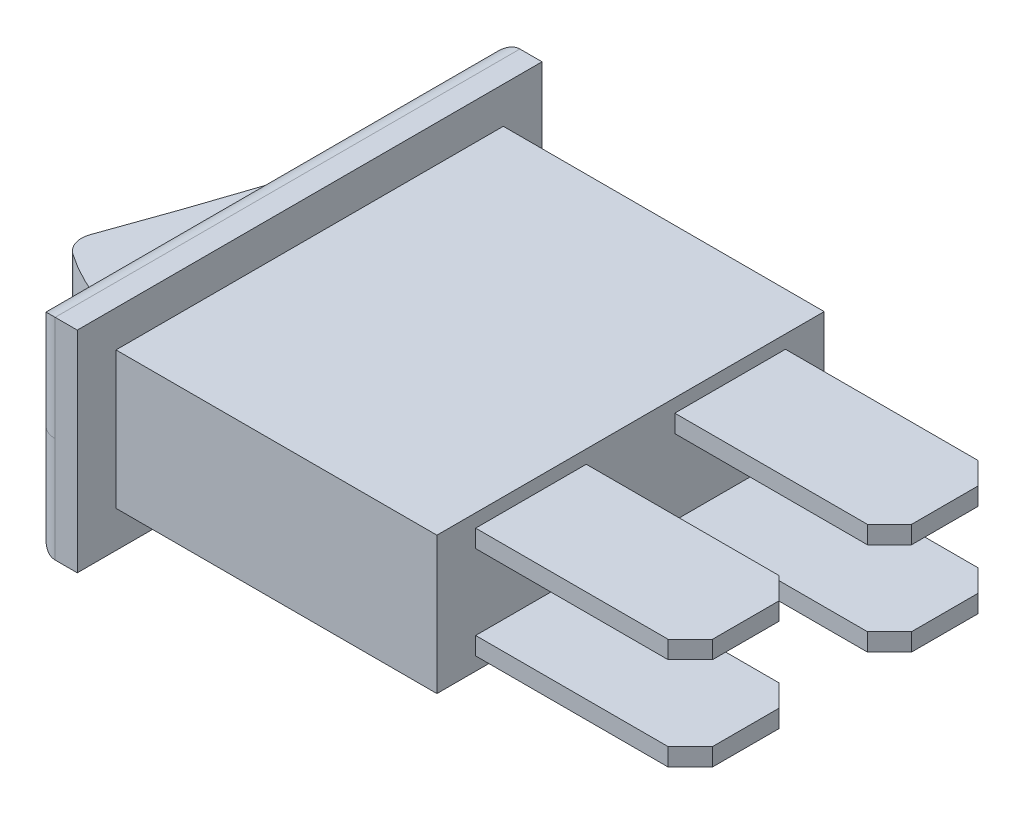
SolidWorks part; units mm, degrees
material "ABS"
ref_plane "Plan de face" through (0, 0, 0) normal (0, 0, 1) x (1, 0, 0)
ref_plane "Plan de dessus" through (0, 0, 0) normal (0, 1, 0) x (1, 0, 0)
ref_plane "Plan de droite" through (0, 0, 0) normal (1, 0, 0) x (0, 0, -1)
sketch "Esquisse1" plane through (0, 0, 0) normal (0, 1, 0) x (1, 0, 0)
  line L0 (0, 0) -> (0, 1.75)
  line L1 (0, 0) -> (14.5, 0)
  line L3 (0, -17.5) -> (14.5, -17.5)
  line L4 (14.5, 0) -> (14.5, -17.5)
  line L5 (0, 1.75) -> (-2, 1.75)
  line L6 (-2, 1.75) -> (-2, -4.3319)
  line L7 (-2, -19.25) -> (0, -19.25)
  line L8 (0, -19.25) -> (0, -17.5)
  line L9 (14.5, -8.75) -> (0, -8.75) construction
  line L10 (0, -8.75) -> (-2, -8.75) construction
  line L11 (-2, -16.065) -> (-2, -19.25)
  arc A0 (-4.7181, -14.73) -> (-2, -16.065) centre (1.1152, -6.2883) ccw
  arc A1 (-5.0893, -13.5653) -> (-2, -4.3319) centre (-180.0974, 50.123) ccw
  arc A2 (-5.0893, -13.5653) -> (-4.7181, -14.73) centre (-4.1496, -13.9073) ccw
  dimension "D5" = 1
  dimension "D1" = 14.5
  dimension "D2" = 17.5
  dimension "D3" = 2
  dimension "D4" = 21
extrude "Boss.-Extru.1" add sketch "Esquisse1" along normal blind 3.1
sketch "Esquisse2" plane through (0, 3.1, 0) normal (0, 1, 0) x (1, 0, 0)
  line L1 (-2, 1.75) -> (0, 1.75)
  line L2 (-2, 1.75) -> (-2, -19.25)
  line L3 (-2, -19.25) -> (0, -19.25)
  line L4 (0, 1.75) -> (0, -19.25)
extrude "Boss.-Extru.2" add sketch "Esquisse2" along normal blind 1.65
sketch "Esquisse3" plane through (14.5, 0, 0) normal (1, 0, 0) x (0, 0, -1)
  line L0 (-10.75, 2.1) -> (-6.75, 2.1) construction
  line L1 (-15.75, 1.7) -> (-10.75, 1.7)
  line L2 (-15.75, 1.7) -> (-15.75, 2.5)
  line L3 (-15.75, 2.5) -> (-10.75, 2.5)
  line L4 (-10.75, 1.7) -> (-10.75, 2.5)
  line L5 (-6.75, 2.5) -> (-1.75, 2.5)
  line L6 (-6.75, 2.5) -> (-6.75, 1.7)
  line L7 (-6.75, 1.7) -> (-1.75, 1.7)
  line L8 (-1.75, 2.5) -> (-1.75, 1.7)
  line L9 (-17.5, 0) -> (0, 0) construction
  line L10 (-8.75, 0) -> (-8.75, 2.1) construction
  line L11 (-13.25, 2.5) -> (-13.25, 1.7) construction
  line L13 (-4.25, 2.5) -> (-4.25, 1.7) construction
  dimension "D1" = 5
  dimension "D2" = 2.1
  dimension "D3" = 0.8
  dimension "D4" = 9
extrude "Boss.-Extru.3" add sketch "Esquisse3" along normal blind 9.7
chamfer "Chanfrein1" distance 1 angle 45 4 edges at (24.2, 2.1, 1.75) (24.2, 2.1, 6.75) (24.2, 2.1, 10.75) (24.2, 2.1, 15.75)
fillet "Congé1" radius 1 3 edges at (-2, 2.375, -1.75) (-2, 4.75, 8.75) (-2, 2.375, 19.25)
mirror "Symétrie1" about plane through (1.1152, 0, 6.2883) normal (0, 1, 0) of "Boss.-Extru.1", "Boss.-Extru.2", "Boss.-Extru.3", "Chanfrein1", "Congé1"
